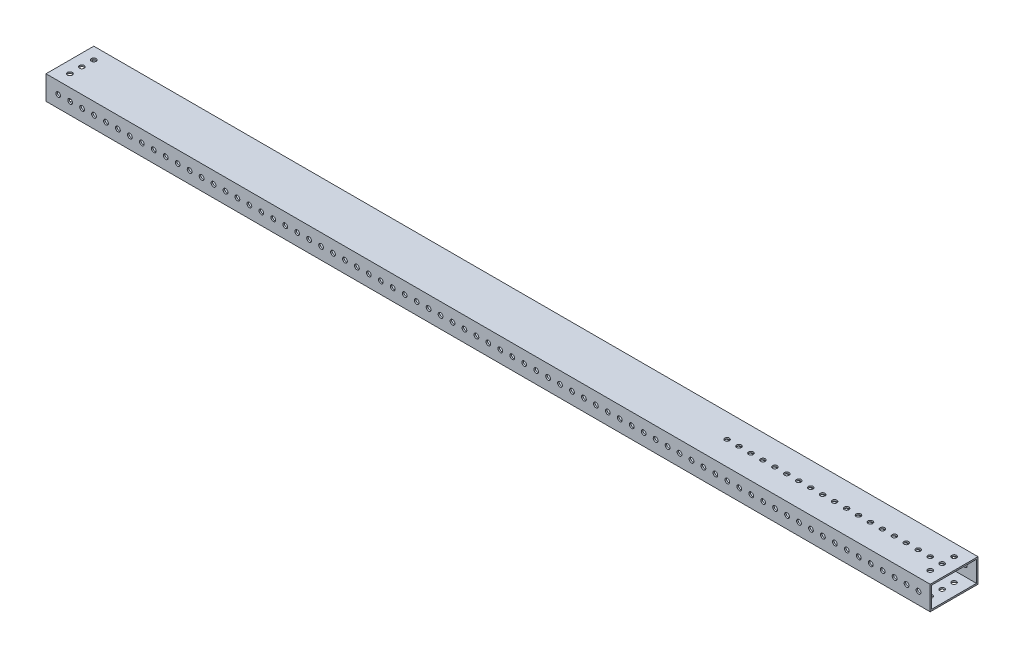
SolidWorks part; units mm, degrees
ref_plane "Front Plane" through (0, 0, 0) normal (0, 0, 1) x (1, 0, 0)
ref_plane "Top Plane" through (0, 0, 0) normal (0, 1, 0) x (1, 0, 0)
ref_plane "Right Plane" through (0, 0, 0) normal (1, 0, 0) x (0, 0, -1)
sketch "Sketch1" plane through (0, 0, 0) normal (0, 1, 0) x (1, 0, 0)
  line L1 (469.9, 25.4) -> (-469.9, 25.4)
  line L2 (469.9, 25.4) -> (469.9, -25.4)
  line L3 (469.9, -25.4) -> (-469.9, -25.4)
  line L4 (-469.9, 25.4) -> (-469.9, -25.4)
  line L5 (469.9, 25.4) -> (-469.9, -25.4) construction
  line L6 (469.9, -25.4) -> (-469.9, 25.4) construction
  circle A0 centre (457.2, 0) radius 2.4892
  circle A1 centre (444.5, 0) radius 2.4892
  circle A2 centre (431.8, 0) radius 2.4892
  circle A3 centre (419.1, 0) radius 2.4892
  circle A4 centre (406.4, 0) radius 2.4892
  circle A5 centre (393.7, 0) radius 2.4892
  circle A6 centre (381, 0) radius 2.4892
  circle A7 centre (368.3, 0) radius 2.4892
  circle A8 centre (355.6, 0) radius 2.4892
  circle A9 centre (342.9, 0) radius 2.4892
  circle A10 centre (330.2, 0) radius 2.4892
  circle A11 centre (317.5, 0) radius 2.4892
  circle A12 centre (304.8, 0) radius 2.4892
  circle A13 centre (292.1, 0) radius 2.4892
  circle A14 centre (279.4, 0) radius 2.4892
  circle A15 centre (266.7, 0) radius 2.4892
  circle A16 centre (254, 0) radius 2.4892
  circle A17 centre (241.3, 0) radius 2.4892
  circle A18 centre (228.6, 0) radius 2.4892
  point P0 (0, 0)
  dimension "D3" = 4.9784
  dimension "D1" = 50.8
  dimension "D2" = 939.8
  dimension "D4" = 12.7
  dimension "D5" = 19
extrude "Boss-Extrude1" add sketch "Sketch1" along normal blind 25.4
sketch "Sketch2" plane through (-469.9, 0, 0) normal (-1, 0, 0) x (0, 0, 1)
  line L1 (23.7937, 23.7836) -> (-23.7836, 23.7836)
  line L2 (23.7937, 23.7836) -> (23.7937, 1.6265)
  line L3 (23.7937, 1.6265) -> (-23.7836, 1.6265)
  line L4 (-23.7836, 23.7836) -> (-23.7836, 1.6265)
  line L6 (-25.4, 25.4) -> (-25.4, 0) construction
  line L7 (25.4, 25.4) -> (25.4, 0) construction
  dimension "D1" = 2.286
  dimension "D2" = 2.286
  dimension "D3" = 1.6164
  dimension "D4" = 1.6063
extrude "Cut-Extrude1" cut sketch "Sketch2" against normal through all
sketch "Sketch3" plane through (0, 0, 25.4) normal (0, 0, 1) x (1, 0, 0)
  line L0 (-1393.7901, 12.7) -> (48606.2099, 12.7) construction
  line L1 (-469.9, 25.4) -> (-469.9, 0) construction
  circle A1 centre (-456.946, 12.7) radius 2.54
  circle A2 centre (-444.246, 12.7) radius 2.54
  circle A3 centre (-431.546, 12.7) radius 2.54
  circle A4 centre (-418.846, 12.7) radius 2.54
  circle A5 centre (-406.146, 12.7) radius 2.54
  circle A6 centre (-393.446, 12.7) radius 2.54
  circle A7 centre (-380.746, 12.7) radius 2.54
  circle A8 centre (-368.046, 12.7) radius 2.54
  circle A9 centre (-355.346, 12.7) radius 2.54
  circle A10 centre (-342.646, 12.7) radius 2.54
  circle A11 centre (-329.946, 12.7) radius 2.54
  circle A12 centre (-317.246, 12.7) radius 2.54
  circle A13 centre (-304.546, 12.7) radius 2.54
  circle A14 centre (-291.846, 12.7) radius 2.54
  circle A15 centre (-279.146, 12.7) radius 2.54
  circle A16 centre (-266.446, 12.7) radius 2.54
  circle A17 centre (-253.746, 12.7) radius 2.54
  circle A18 centre (-241.046, 12.7) radius 2.54
  circle A19 centre (-228.346, 12.7) radius 2.54
  circle A20 centre (-215.646, 12.7) radius 2.54
  circle A21 centre (-202.946, 12.7) radius 2.54
  circle A22 centre (-190.246, 12.7) radius 2.54
  circle A23 centre (-177.546, 12.7) radius 2.54
  circle A24 centre (-164.846, 12.7) radius 2.54
  circle A25 centre (-152.146, 12.7) radius 2.54
  circle A26 centre (-139.446, 12.7) radius 2.54
  circle A27 centre (-126.746, 12.7) radius 2.54
  circle A28 centre (-114.046, 12.7) radius 2.54
  circle A29 centre (-101.346, 12.7) radius 2.54
  circle A30 centre (-88.646, 12.7) radius 2.54
  circle A31 centre (-75.946, 12.7) radius 2.54
  circle A32 centre (-63.246, 12.7) radius 2.54
  circle A33 centre (-50.546, 12.7) radius 2.54
  circle A34 centre (-37.846, 12.7) radius 2.54
  circle A35 centre (-25.146, 12.7) radius 2.54
  circle A36 centre (-12.446, 12.7) radius 2.54
  circle A37 centre (0.254, 12.7) radius 2.54
  circle A38 centre (12.954, 12.7) radius 2.54
  circle A39 centre (25.654, 12.7) radius 2.54
  circle A40 centre (38.354, 12.7) radius 2.54
  circle A41 centre (51.054, 12.7) radius 2.54
  circle A42 centre (63.754, 12.7) radius 2.54
  circle A43 centre (76.454, 12.7) radius 2.54
  circle A44 centre (89.154, 12.7) radius 2.54
  circle A45 centre (101.854, 12.7) radius 2.54
  circle A46 centre (114.554, 12.7) radius 2.54
  circle A47 centre (127.254, 12.7) radius 2.54
  circle A48 centre (139.954, 12.7) radius 2.54
  circle A49 centre (152.654, 12.7) radius 2.54
  circle A50 centre (165.354, 12.7) radius 2.54
  circle A51 centre (178.054, 12.7) radius 2.54
  circle A52 centre (190.754, 12.7) radius 2.54
  circle A53 centre (203.454, 12.7) radius 2.54
  circle A54 centre (216.154, 12.7) radius 2.54
  circle A55 centre (228.854, 12.7) radius 2.54
  circle A56 centre (241.554, 12.7) radius 2.54
  circle A57 centre (254.254, 12.7) radius 2.54
  circle A58 centre (266.954, 12.7) radius 2.54
  circle A59 centre (279.654, 12.7) radius 2.54
  circle A60 centre (292.354, 12.7) radius 2.54
  circle A61 centre (305.054, 12.7) radius 2.54
  circle A62 centre (317.754, 12.7) radius 2.54
  circle A63 centre (330.454, 12.7) radius 2.54
  circle A64 centre (343.154, 12.7) radius 2.54
  circle A65 centre (355.854, 12.7) radius 2.54
  circle A66 centre (368.554, 12.7) radius 2.54
  circle A67 centre (381.254, 12.7) radius 2.54
  circle A68 centre (393.954, 12.7) radius 2.54
  circle A69 centre (406.654, 12.7) radius 2.54
  circle A70 centre (419.354, 12.7) radius 2.54
  circle A71 centre (432.054, 12.7) radius 2.54
  circle A72 centre (444.754, 12.7) radius 2.54
  circle A73 centre (457.454, 12.7) radius 2.54
  point P5 (-469.9, 12.7)
  dimension "D1" = 5.08
  dimension "D2" = 12.954
  dimension "D4" = 12.7
  dimension "D6" = 12.7
  dimension "D3" = 60
  dimension "D5" = 14
extrude "Cut-Extrude2" cut sketch "Sketch3" against normal through all
sketch "Sketch4" plane through (0, 25.4, 0) normal (0, 1, 0) x (1, 0, 0)
  line L0 (-1393.7901, 0) -> (48606.2099, 0) construction
  line L1 (-469.9, 25.4) -> (-469.9, -25.4) construction
  line L2 (-1388.247, 12.7) -> (48611.753, 12.7) construction
  line L3 (-1379.4121, -12.7) -> (48620.5879, -12.7) construction
  line L4 (-469.9, -25.4) -> (469.9, -25.4) construction
  line L5 (0, 25.4) -> (0, -25.4) construction
  line L6 (469.9, 25.4) -> (-469.9, 25.4) construction
  circle A0 centre (-457.2, 12.7) radius 2.54
  circle A2 centre (-457.2, -12.7) radius 2.54
  circle A3 centre (-457.2, 0) radius 2.54
  circle A4 centre (457.2, 12.7) radius 2.54
  circle A5 centre (457.2, 0) radius 2.54
  circle A6 centre (457.2, -12.7) radius 2.54
  point P5 (-469.9, 0)
  dimension "D1" = 5.08
  dimension "D5" = 12.7
  dimension "D6" = 5.08
  dimension "D2" = 12.7
  dimension "D3" = 12.7
  dimension "D4" = 12.7
extrude "Cut-Extrude3" cut sketch "Sketch4" against normal through all
